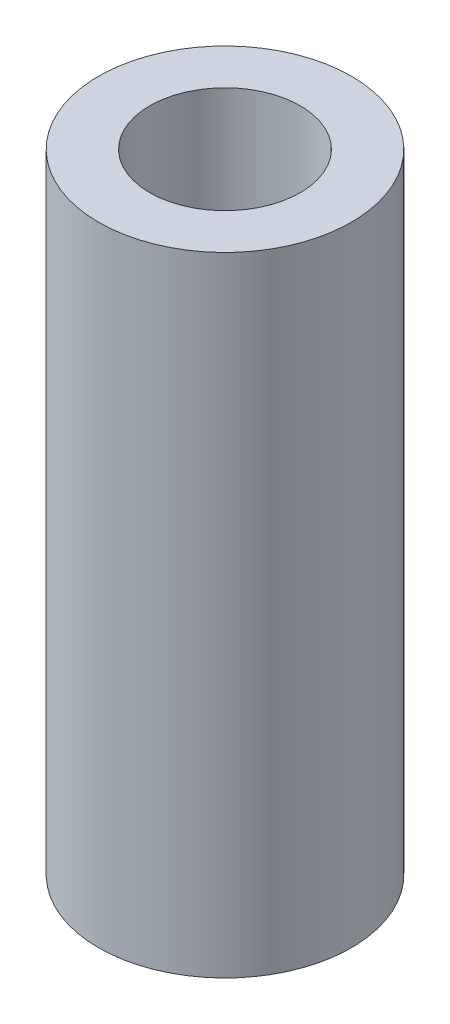
SolidWorks part; units mm, degrees
ref_plane "Front Plane" through (0, 0, 0) normal (0, 0, 1) x (1, 0, 0)
ref_plane "Top Plane" through (0, 0, 0) normal (0, 1, 0) x (1, 0, 0)
ref_plane "Right Plane" through (0, 0, 0) normal (1, 0, 0) x (0, 0, -1)
sketch "Sketch1" plane through (0, 0, 0) normal (0, 1, 0) x (1, 0, 0)
  circle A0 centre (0, 0) radius 3.2
  dimension "D1" = 6.4
extrude "Boss-Extrude1" add sketch "Sketch1" along normal blind 15.9
sketch "Sketch2" plane through (0, 15.9, 0) normal (0, 1, 0) x (1, 0, 0)
  circle A0 centre (0, 0) radius 1.905
  circle A1 centre (0, 0) radius 3.2 construction
  dimension "D1" = 3.81
extrude "Cut-Extrude1" cut sketch "Sketch2" against normal through all
